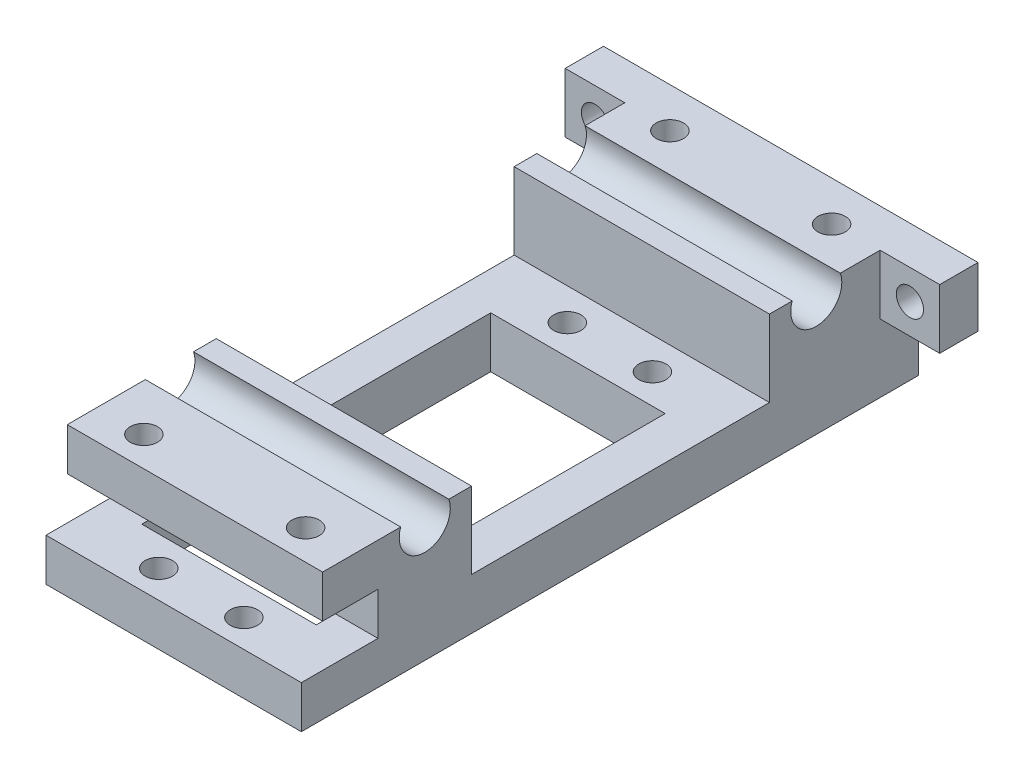
SolidWorks part; units mm, degrees
ref_plane "Front Plane" through (0, 0, 0) normal (0, 0, 1) x (1, 0, 0)
ref_plane "Top Plane" through (0, 0, 0) normal (0, 1, 0) x (1, 0, 0)
ref_plane "Right Plane" through (0, 0, 0) normal (1, 0, 0) x (0, 0, -1)
sketch "Sketch1" plane through (0, 0, 0) normal (0, 1, 0) x (1, 0, 0)
  line L1 (-15, -36.25) -> (15, -36.25)
  line L2 (-15, -36.25) -> (-15, 36.25)
  line L3 (-15, 36.25) -> (15, 36.25)
  line L4 (15, -36.25) -> (15, 36.25)
  line L5 (-15, -36.25) -> (15, 36.25) construction
  line L6 (-15, 36.25) -> (15, -36.25) construction
  point P0 (0, 0)
  dimension "D1" = 72.5
  dimension "D2" = 30
extrude "Boss-Extrude1" add sketch "Sketch1" along normal blind 15
sketch "Sketch2" plane through (0, 0, 0) normal (0, -1, 0) x (1, 0, 0)
  line L0 (-15, 36.25) -> (15, 36.25) construction
  line L1 (-10.5, 29.5) -> (10, 29.5)
  line L2 (-10.5, 29.5) -> (-10.5, -11.5)
  line L3 (-10.5, -11.5) -> (10, -11.5)
  line L4 (10, 29.5) -> (10, -11.5)
  line L5 (-10.5, 29.5) -> (10, -11.5) construction
  line L6 (-10.5, -11.5) -> (10, 29.5) construction
  line L7 (15, 36.25) -> (15, -36.25) construction
  point P0 (-0.25, 9)
  dimension "D1" = 6.75
  dimension "D2" = 5
  dimension "D3" = 41
  dimension "D4" = 20.5
extrude "Cut-Extrude1" cut sketch "Sketch2" against normal blind 8 contours L4 L3 L2 L1
sketch "Sketch3" plane through (0, 15, 0) normal (0, 1, 0) x (1, 0, 0)
  line L0 (-15, 36.25) -> (-15, -36.25) construction
  line L1 (-15, -16.25) -> (15, -16.25)
  line L2 (-15, -16.25) -> (-15, 18.75)
  line L3 (-15, 18.75) -> (15, 18.75)
  line L4 (15, -16.25) -> (15, 18.75)
  line L5 (15, -36.25) -> (15, 36.25) construction
  line L6 (-15, -36.25) -> (15, -36.25) construction
  dimension "D1" = 35
  dimension "D2" = 20
extrude "Cut-Extrude2" cut sketch "Sketch3" against normal blind 9
sketch "Sketch4" plane through (15, 0, 0) normal (1, 0, 0) x (0, 0, -1)
  line L0 (-33.75, 15) -> (-33.75, 10)
  line L1 (-36.25, 15) -> (-16.25, 15) construction
  line L2 (-33.75, 10) -> (-27.25, 10)
  line L3 (-27.25, 10) -> (-27.25, 5)
  line L4 (-27.25, 5) -> (-36.25, 5)
  line L5 (-36.25, 15) -> (-36.25, 0) construction
  line L6 (-36.25, 5) -> (-36.25, 15)
  line L7 (-36.25, 15) -> (-33.75, 15)
  line L8 (-36.25, 0) -> (36.25, 0) construction
  dimension "D1" = 2.5
  dimension "D2" = 9
  dimension "D3" = 5
  dimension "D4" = 5
extrude "Cut-Extrude3" cut sketch "Sketch4" against normal through all
sketch "Sketch5" plane through (0, 0, 0) normal (0, -1, 0) x (1, 0, 0)
  line L0 (-10.5, -11.5) -> (10, -11.5) construction
  line L2 (-10.5, 29.5) -> (10, 29.5) construction
  circle A0 centre (-5, 33) radius 1.6
  circle A1 centre (5, 33) radius 1.6
  circle A2 centre (-5, -15) radius 1.6
  circle A3 centre (5, -15) radius 1.6
  point P8 (0, 0)
  point P9 (0, 0)
  point P10 (0, 0)
  point P11 (0, 0)
  point P15 (0, 0)
  point P19 (-5.3371, -14.5309)
  dimension "D1" = 3.2
  dimension "D2" = 3.2
  dimension "D3" = 3.2
  dimension "D4" = 3.2
  dimension "D5" = 10
  dimension "D6" = 5
  dimension "D7" = 3.5
  dimension "D8" = 3.5
extrude "Cut-Extrude4" cut sketch "Sketch5" against normal up to next
sketch "Sketch6" plane through (15, 0, 0) normal (1, 0, 0) x (0, 0, -1)
  line L0 (18.75, 15) -> (36.25, 15) construction
  line L1 (36.25, 15) -> (36.25, 0) construction
  circle A0 centre (24.25, 14) radius 3
  circle A1 centre (-21.75, 14) radius 3
  point P4 (0, 0)
  dimension "D2" = 6
  dimension "D3" = 6
  dimension "D1" = 1
  dimension "D4" = 12
  dimension "D5" = 46
extrude "Cut-Extrude5" cut sketch "Sketch6" against normal through all
sketch "Sketch7" plane through (0, 15, 0) normal (0, 1, 0) x (1, 0, 0)
  line L0 (15, -33.75) -> (15, -24.5784) construction
  line L1 (-15, -24.5784) -> (-15, -33.75) construction
  line L2 (-15, -33.75) -> (15, -33.75) construction
  line L3 (15, 36.25) -> (-15, 36.25) construction
  circle A0 centre (-9.5, -30.25) radius 1.6
  circle A1 centre (9.5, -30.25) radius 1.6
  circle A2 centre (-9.5, 31.55) radius 1.6
  circle A3 centre (9.5, 31.55) radius 1.6
  point P14 (0, 0)
  point P15 (0, 0)
  point P18 (0, 0)
  dimension "D1" = 3.2
  dimension "D2" = 3.2
  dimension "D3" = 5.5
  dimension "D6" = 3.2
  dimension "D7" = 3.2
  dimension "D4" = 5.5
  dimension "D5" = 3.5
  dimension "D8" = 4.7
extrude "Cut-Extrude6" cut sketch "Sketch7" against normal up to next
sketch "Sketch8" plane through (0, 0, -36.25) normal (0, 0, -1) x (-1, 0, 0)
  line L1 (15, 15) -> (22, 15)
  line L2 (15, 15) -> (15, 8)
  line L3 (15, 8) -> (22, 8)
  line L4 (22, 15) -> (22, 8)
  line L5 (-15, 15) -> (-22, 15)
  line L6 (-15, 15) -> (-15, 8)
  line L7 (-15, 8) -> (-22, 8)
  line L8 (-22, 15) -> (-22, 8)
  dimension "D1" = 7
  dimension "D2" = 7
  dimension "D3" = 7
  dimension "D4" = 7
extrude "Boss-Extrude2" add sketch "Sketch8" against normal blind 4.5
sketch "Sketch9" plane through (0, 0, -36.25) normal (0, 0, -1) x (-1, 0, 0)
  line L0 (-22, 15) -> (22, 15) construction
  line L1 (22, 8) -> (22, 15) construction
  line L2 (-22, 15) -> (-22, 8) construction
  line L3 (-22, 8) -> (-15, 8) construction
  circle A0 centre (18.5, 11.5) radius 1.6
  circle A1 centre (-18.5, 11.5) radius 1.6
  point P8 (21.6492, 11.0991)
  dimension "D1" = 3.2
  dimension "D2" = 3.2
  dimension "D3" = 3.5
  dimension "D4" = 3.5
  dimension "D5" = 3.5
  dimension "D6" = 3.5
extrude "Cut-Extrude7" cut sketch "Sketch9" against normal up to next
